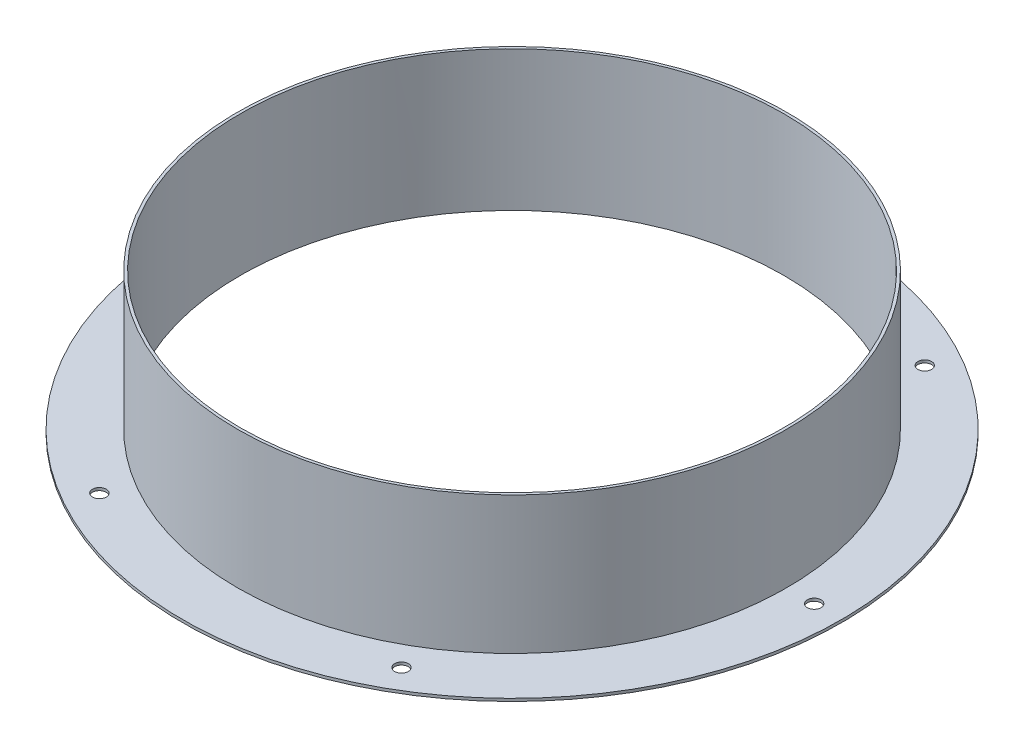
SolidWorks part; units mm, degrees
ref_plane "Front Plane" through (0, 0, 0) normal (0, 0, 1) x (1, 0, 0)
ref_plane "Top Plane" through (0, 0, 0) normal (0, 1, 0) x (1, 0, 0)
ref_plane "Right Plane" through (0, 0, 0) normal (1, 0, 0) x (0, 0, -1)
sketch "Sketch1" plane through (0, 0, 0) normal (0, 1, 0) x (1, 0, 0)
  circle A0 centre (0, 0) radius 100
  circle A1 centre (0, 0) radius 99
  dimension "D1" = 200
  dimension "D2" = 1
extrude "Boss-Extrude1" add sketch "Sketch1" along normal blind 50
sketch "Sketch2" plane through (0, 0, 0) normal (0, -1, 0) x (1, 0, 0)
  circle A0 centre (0, 0) radius 99
  circle A1 centre (0, 0) radius 120
  dimension "D1" = 240
extrude "Boss-Extrude2" add sketch "Sketch2" along normal blind 1
sketch "Sketch3" plane through (0, 0, 0) normal (0, 1, 0) x (1, 0, 0)
  line L0 (-120, 0) -> (-100, 0) construction
  circle A0 centre (0, 0) radius 120 construction
  circle A1 centre (0, 0) radius 100 construction
  circle A2 centre (-110, 0) radius 2.5
  circle A3 centre (-55, 95.2628) radius 2.5
  circle A4 centre (55, 95.2628) radius 2.5
  circle A5 centre (110, 0) radius 2.5
  circle A6 centre (55, -95.2628) radius 2.5
  circle A7 centre (-55, -95.2628) radius 2.5
  point P21 (0, 0)
  dimension "D1" = 5
  dimension "D2" = 6
extrude "Cut-Extrude1" cut sketch "Sketch3" against normal blind 1
